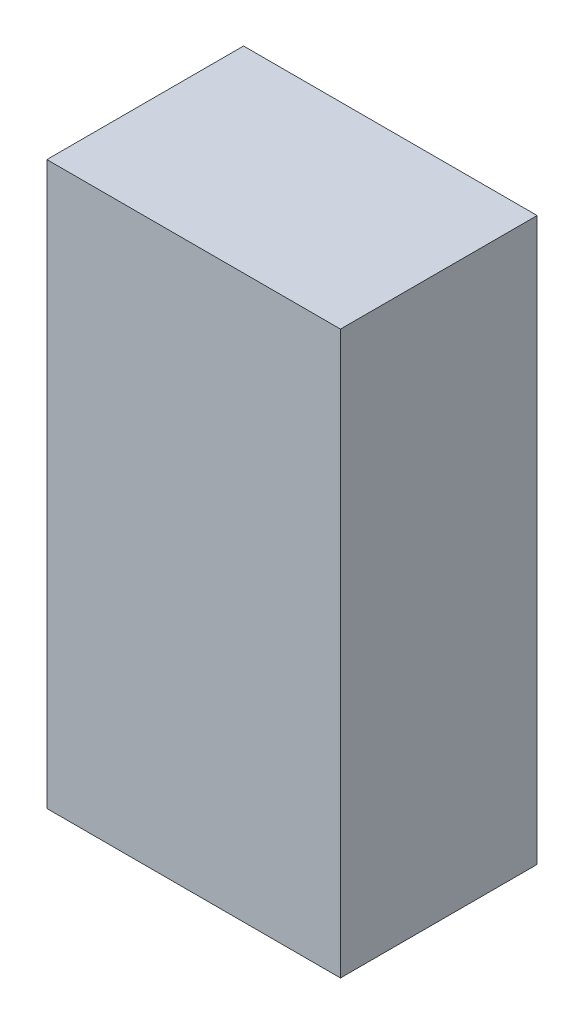
SolidWorks part; units mm, degrees
ref_plane "Front Plane" through (0, 0, 0) normal (0, 0, 1) x (1, 0, 0)
ref_plane "Top Plane" through (0, 0, 0) normal (0, 1, 0) x (1, 0, 0)
ref_plane "Right Plane" through (0, 0, 0) normal (1, 0, 0) x (0, 0, -1)
sketch "Sketch1" plane through (0, 0, 0) normal (0, 1, 0) x (1, 0, 0)
  line L1 (-12.8, -8.575) -> (12.8, -8.575)
  line L2 (-12.8, -8.575) -> (-12.8, 8.575)
  line L3 (-12.8, 8.575) -> (12.8, 8.575)
  line L4 (12.8, -8.575) -> (12.8, 8.575)
  line L5 (-12.8, -8.575) -> (12.8, 8.575) construction
  line L6 (-12.8, 8.575) -> (12.8, -8.575) construction
  point P0 (0, 0)
  dimension "D1" = 17.15
  dimension "D2" = 25.6
extrude "Boss-Extrude1" add sketch "Sketch1" along normal blind 49
